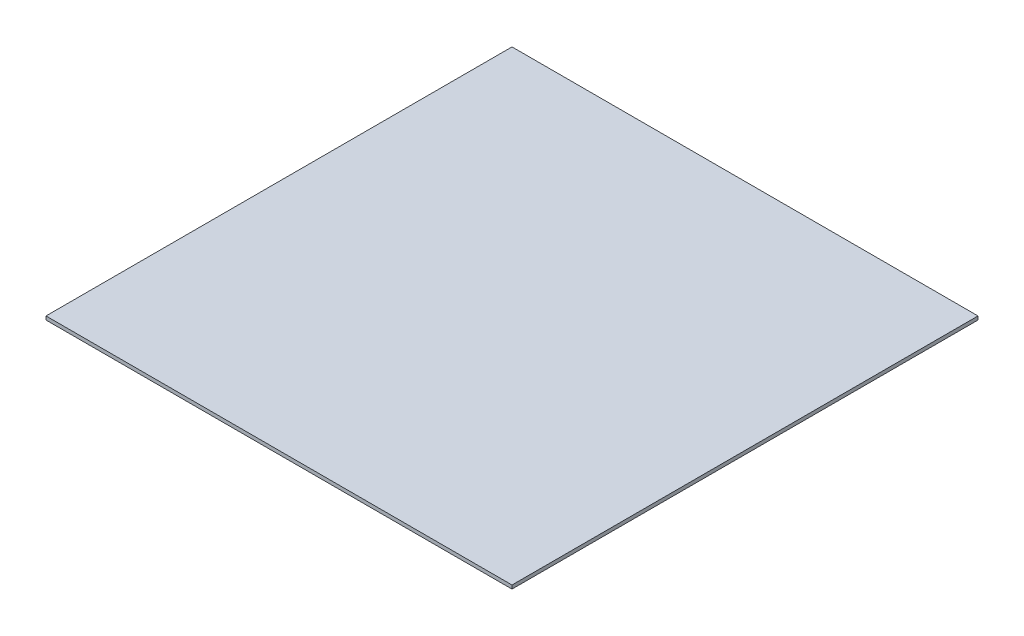
SolidWorks part; units mm, degrees
ref_plane "Alzado" through (0, 0, 0) normal (0, 0, 1) x (1, 0, 0)
ref_plane "Planta" through (0, 0, 0) normal (0, 1, 0) x (1, 0, 0)
ref_plane "Vista lateral" through (0, 0, 0) normal (1, 0, 0) x (0, 0, -1)
sketch "Croquis1" plane through (0, 0, 0) normal (0, 1, 0) x (1, 0, 0)
  line L1 (-195, 195) -> (195, 195)
  line L2 (-195, 195) -> (-195, -195)
  line L3 (-195, -195) -> (195, -195)
  line L4 (195, 195) -> (195, -195)
  line L5 (-195, 195) -> (195, -195) construction
  line L6 (-195, -195) -> (195, 195) construction
  point P0 (0, 0)
extrude "Saliente-Extruir1" add sketch "Croquis1" along normal blind 3
